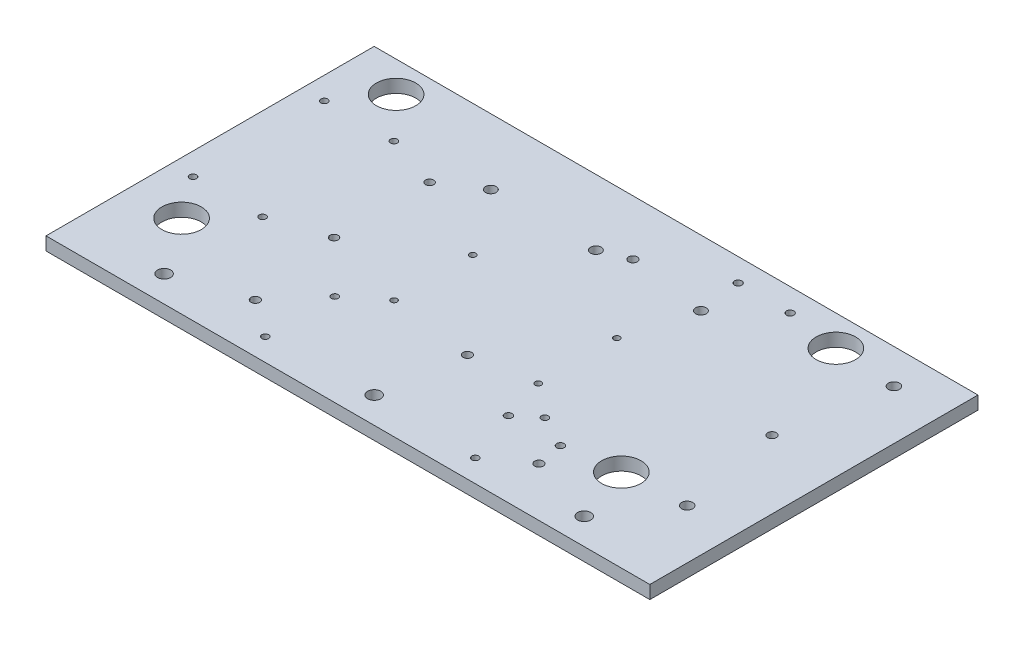
SolidWorks part; units mm, degrees
ref_plane "Front Plane" through (0, 0, 0) normal (0, 0, 1) x (1, 0, 0)
ref_plane "Top Plane" through (0, 0, 0) normal (0, 1, 0) x (1, 0, 0)
ref_plane "Right Plane" through (0, 0, 0) normal (1, 0, 0) x (0, 0, -1)
sketch "Sketch1" plane through (0, 0, 0) normal (0, 1, 0) x (1, 0, 0)
  line L1 (0, 0) -> (292.1, 0)
  line L2 (0, 0) -> (0, 158.75)
  line L3 (0, 158.75) -> (292.1, 158.75)
  line L4 (292.1, 0) -> (292.1, 158.75)
  dimension "D1" = 292.1
  dimension "D2" = 158.75
extrude "Boss-Extrude1" add sketch "Sketch1" along normal blind 6.35
sketch "Sketch2" plane through (0, 6.35, 0) normal (0, 1, 0) x (1, 0, 0)
  line L0 (0, 25.4) -> (292.1, 25.4) construction
  line L1 (0, 12.7) -> (292.1, 12.7) construction
  line L2 (146.05, 0) -> (146.05, 158.75) construction
  line L4 (0, 158.75) -> (0, 0)
  line L5 (0, 0) -> (292.1, 0)
  line L6 (292.1, 0) -> (292.1, 158.75)
  line L7 (292.1, 158.75) -> (0, 158.75)
  line L8 (0, 158.75) -> (0, 0) construction
  line L9 (0, 0) -> (292.1, 0) construction
  line L10 (292.1, 0) -> (292.1, 158.75) construction
  line L11 (292.1, 158.75) -> (0, 158.75) construction
  circle A0 centre (146.05, 12.7) radius 3.175
  circle A1 centre (247.65, 12.7) radius 3.175
  circle A2 centre (44.45, 12.7) radius 3.175
  dimension "D6" = 6.35
  dimension "D7" = 6.35
  dimension "D8" = 6.35
  dimension "D2" = 25.4
  dimension "D3" = 12.7
  dimension "D4" = 101.6
  dimension "D5" = 101.6
  dimension "D1" = 0
extrude "Cut-Extrude2" cut sketch "Sketch2" against normal blind 6.35
sketch "Sketch5" [suppressed] plane through (0, 6.35, 0) normal (0, 1, 0) x (1, 0, 0)
  line L0 (0, 0) -> (292.1, 0) construction
  line L1 (279.4, 31.75) -> (143.9, 31.75) construction
  line L2 (279.4, 31.75) -> (279.4, 75.25) construction
  line L3 (279.4, 75.25) -> (143.9, 75.25) construction
  line L4 (143.9, 31.75) -> (143.9, 75.25) construction
  line L5 (292.1, 0) -> (292.1, 158.75) construction
  circle A0 centre (279.4, 31.75) radius 1.525
  circle A1 centre (279.4, 75.25) radius 1.525
  circle A2 centre (143.9, 75.25) radius 1.525
  circle A3 centre (143.9, 31.75) radius 1.525
  dimension "D3" = 3.05
  dimension "D1" = 43.5
  dimension "D2" = 135.5
  dimension "D4" = 31.75
  dimension "D5" = 12.7
sketch "Sketch6" plane through (0, 6.35, 0) normal (0, 1, 0) x (1, 0, 0)
  line L0 (238.125, 158.75) -> (238.125, 0) construction
  line L1 (292.1, 158.75) -> (0, 158.75) construction
  line L2 (0, 0) -> (292.1, 0) construction
  line L4 (146.05, 158.75) -> (146.05, 0) construction
  line L5 (0, 25.4) -> (292.1, 25.4) construction
  line L6 (0, 158.75) -> (0, 0) construction
  line L7 (292.1, 0) -> (292.1, 158.75) construction
  line L8 (25.4, 40.1879) -> (238.125, 40.1879) construction
  line L9 (25.4, 143.9621) -> (238.125, 143.9621) construction
  line L10 (0, 92.075) -> (292.1, 92.075) construction
  line L11 (0, 158.75) -> (0, 25.4) construction
  line L12 (25.4, 143.9621) -> (25.4, 92.075) construction
  line L13 (25.4, 92.075) -> (25.4, 40.1879) construction
  circle A0 centre (25.4, 40.1879) radius 9.525
  circle A1 centre (238.125, 40.1879) radius 9.525
  circle A2 centre (25.4, 143.9621) radius 9.525
  circle A3 centre (238.125, 143.9621) radius 9.525
  point P6 (0, 0)
  dimension "D2" = 19.05
  dimension "D3" = 19.05
  dimension "D1" = 25.4
  dimension "D4" = 25.4
  dimension "D5" = 53.975
extrude "Cut-Extrude3" cut sketch "Sketch6" against normal through all
sketch "Sketch8" plane through (0, 6.35, 0) normal (0, 1, 0) x (1, 0, 0)
  line L0 (265.43, 121.908) -> (265.43, 112.242) construction
  line L1 (270.764, 112.242) -> (270.764, 121.908) construction
  line L2 (265.43, 96.908) -> (265.43, 87.242)
  line L3 (270.764, 87.242) -> (270.764, 96.908)
  line L4 (265.43, 96.908) -> (265.43, 87.242) construction
  line L5 (270.764, 87.242) -> (270.764, 96.908) construction
  line L6 (265.43, 146.908) -> (265.43, 137.242) construction
  line L7 (270.764, 137.242) -> (270.764, 146.908) construction
  line L8 (265.43, 96.908) -> (265.43, 87.242) construction
  line L9 (270.764, 87.242) -> (270.764, 96.908) construction
  line L10 (265.43, 121.908) -> (265.43, 112.242) construction
  line L11 (270.764, 112.242) -> (270.764, 121.908) construction
  line L12 (265.43, 71.908) -> (265.43, 62.242) construction
  line L13 (270.764, 62.242) -> (270.764, 71.908) construction
  line L14 (265.43, 96.908) -> (265.43, 87.242) construction
  line L15 (270.764, 87.242) -> (270.764, 96.908) construction
  line L16 (265.43, 71.908) -> (265.43, 62.242) construction
  line L17 (270.764, 62.242) -> (270.764, 71.908) construction
  line L18 (265.43, 46.908) -> (265.43, 37.242) construction
  line L19 (270.764, 37.242) -> (270.764, 46.908) construction
  line L20 (265.43, 96.908) -> (265.43, 121.908) construction
  line L21 (268.097, 137.242) -> (268.097, 146.908) construction
  line L22 (268.097, 37.242) -> (268.097, 46.908) construction
  line L23 (143.764, 129.54) -> (134.239, 129.54) construction
  line L24 (134.239, 124.46) -> (143.764, 124.46) construction
  line L25 (213.1283, 38.3159) -> (211.5027, 38.3159)
  line L26 (211.5027, 34.7345) -> (213.1283, 34.7345)
  line L27 (222.285, 31.6611) -> (222.285, 152.4889)
  line L28 (222.285, 152.4889) -> (177.2, 152.4889)
  line L29 (177.2, 152.4889) -> (177.2, 31.6611)
  line L30 (177.2, 31.6611) -> (222.285, 31.6611)
  line L31 (222.285, 31.6611) -> (222.285, 152.4889) construction
  line L32 (222.285, 152.4889) -> (177.2, 152.4889) construction
  line L33 (177.2, 152.4889) -> (177.2, 31.6611) construction
  line L34 (177.2, 31.6611) -> (222.285, 31.6611) construction
  line L35 (213.1283, 38.3159) -> (211.5027, 38.3159) construction
  line L36 (211.5027, 34.7345) -> (213.1283, 34.7345) construction
  line L37 (187.9823, 38.3159) -> (186.3567, 38.3159)
  line L38 (186.3567, 34.7345) -> (187.9823, 34.7345)
  line L39 (187.9823, 38.3159) -> (186.3567, 38.3159) construction
  line L40 (186.3567, 34.7345) -> (187.9823, 34.7345) construction
  line L41 (211.5027, 145.8341) -> (213.1283, 145.8341)
  line L42 (213.1283, 149.4155) -> (211.5027, 149.4155)
  line L43 (211.5027, 145.8341) -> (213.1283, 145.8341) construction
  line L44 (213.1283, 149.4155) -> (211.5027, 149.4155) construction
  line L45 (186.3567, 145.8341) -> (187.9823, 145.8341)
  line L46 (187.9823, 149.4155) -> (186.3567, 149.4155)
  line L47 (186.3567, 145.8341) -> (187.9823, 145.8341) construction
  line L48 (187.9823, 149.4155) -> (186.3567, 149.4155) construction
  line L49 (194.564, 129.54) -> (185.039, 129.54)
  line L50 (185.039, 124.46) -> (194.564, 124.46)
  line L51 (194.564, 129.54) -> (185.039, 129.54) construction
  line L52 (185.039, 124.46) -> (194.564, 124.46) construction
  line L53 (92.964, 129.54) -> (83.439, 129.54) construction
  line L54 (83.439, 124.46) -> (92.964, 124.46) construction
  line L55 (194.564, 129.54) -> (143.764, 129.54) construction
  line L56 (83.439, 127) -> (194.564, 127) construction
  line L57 (189.8015, 124.46) -> (189.8015, 129.54) construction
  line L58 (88.2015, 124.46) -> (88.2015, 129.54) construction
  line L63 (109.05, 54.7) -> (183.05, 54.7)
  line L64 (183.05, 54.7) -> (183.05, 97.7)
  line L65 (183.05, 97.7) -> (109.05, 97.7)
  line L66 (109.05, 97.7) -> (109.05, 54.7)
  line L67 (109.05, 54.7) -> (183.05, 54.7) construction
  line L68 (183.05, 54.7) -> (183.05, 97.7) construction
  line L69 (183.05, 97.7) -> (109.05, 97.7) construction
  line L70 (109.05, 97.7) -> (109.05, 54.7) construction
  line L82 (186.3567, 36.5252) -> (187.9823, 36.5252) construction
  line L83 (211.5027, 36.5252) -> (213.1283, 36.5252) construction
  line L84 (211.5027, 147.6248) -> (213.1283, 147.6248) construction
  line L85 (186.3567, 147.6248) -> (187.9823, 147.6248) construction
  line L88 (70.3882, 66.9707) -> (81.4118, 66.9707)
  line L89 (81.4118, 70.9077) -> (70.3882, 70.9077)
  line L90 (70.3882, 66.9707) -> (81.4118, 66.9707) construction
  line L91 (81.4118, 70.9077) -> (70.3882, 70.9077) construction
  line L92 (77.8685, 63.0845) -> (77.8685, 68.9392)
  line L93 (73.9315, 68.9392) -> (73.9315, 63.0845)
  line L94 (126.4, 44.9707) -> (126.4, 139.1793)
  line L95 (25.4, 44.9707) -> (126.4, 44.9707)
  line L96 (25.4, 139.1793) -> (25.4, 44.9707)
  line L97 (126.4, 139.1793) -> (25.4, 139.1793)
  line L98 (126.4, 44.9707) -> (126.4, 139.1793) construction
  line L99 (25.4, 44.9707) -> (126.4, 44.9707) construction
  line L100 (25.4, 139.1793) -> (25.4, 44.9707) construction
  line L101 (126.4, 139.1793) -> (25.4, 139.1793) construction
  line L102 (77.8685, 63.0845) -> (77.8685, 68.9392) construction
  line L103 (73.9315, 68.9392) -> (73.9315, 63.0845) construction
  line L104 (73.9315, 115.2108) -> (73.9315, 109.3561)
  line L105 (77.8685, 109.3561) -> (77.8685, 115.2108)
  line L106 (73.9315, 115.2108) -> (73.9315, 109.3561) construction
  line L107 (77.8685, 109.3561) -> (77.8685, 115.2108) construction
  line L108 (70.3882, 113.2423) -> (81.4118, 113.2423)
  line L109 (81.4118, 117.1793) -> (70.3882, 117.1793)
  line L110 (70.3882, 113.2423) -> (81.4118, 113.2423) construction
  line L111 (81.4118, 117.1793) -> (70.3882, 117.1793) construction
  arc A0 (265.43, 112.242) -> (270.764, 112.242) centre (268.097, 112.242) ccw construction
  arc A1 (270.764, 121.908) -> (265.43, 121.908) centre (268.097, 121.908) ccw construction
  arc A2 (265.43, 87.242) -> (270.764, 87.242) centre (268.097, 87.242) ccw
  arc A3 (270.764, 96.908) -> (265.43, 96.908) centre (268.097, 96.908) ccw
  arc A4 (265.43, 87.242) -> (270.764, 87.242) centre (268.097, 87.242) ccw construction
  arc A5 (270.764, 96.908) -> (265.43, 96.908) centre (268.097, 96.908) ccw construction
  arc A6 (265.43, 137.242) -> (270.764, 137.242) centre (268.097, 137.242) ccw construction
  arc A7 (270.764, 146.908) -> (265.43, 146.908) centre (268.097, 146.908) ccw construction
  arc A8 (265.43, 87.242) -> (270.764, 87.242) centre (268.097, 87.242) ccw construction
  arc A9 (270.764, 96.908) -> (265.43, 96.908) centre (268.097, 96.908) ccw construction
  arc A10 (265.43, 112.242) -> (270.764, 112.242) centre (268.097, 112.242) ccw construction
  arc A11 (270.764, 121.908) -> (265.43, 121.908) centre (268.097, 121.908) ccw construction
  arc A12 (265.43, 62.242) -> (270.764, 62.242) centre (268.097, 62.242) ccw construction
  arc A13 (270.764, 71.908) -> (265.43, 71.908) centre (268.097, 71.908) ccw construction
  arc A14 (265.43, 87.242) -> (270.764, 87.242) centre (268.097, 87.242) ccw construction
  arc A15 (270.764, 96.908) -> (265.43, 96.908) centre (268.097, 96.908) ccw construction
  arc A16 (265.43, 62.242) -> (270.764, 62.242) centre (268.097, 62.242) ccw construction
  arc A17 (270.764, 71.908) -> (265.43, 71.908) centre (268.097, 71.908) ccw construction
  arc A18 (265.43, 37.242) -> (270.764, 37.242) centre (268.097, 37.242) ccw construction
  arc A19 (270.764, 46.908) -> (265.43, 46.908) centre (268.097, 46.908) ccw construction
  circle A20 centre (268.097, 42.075) radius 2.667
  circle A21 centre (268.097, 142.075) radius 2.667
  arc A22 (134.239, 129.54) -> (134.239, 124.46) centre (134.239, 127) ccw construction
  arc A23 (143.764, 124.46) -> (143.764, 129.54) centre (143.764, 127) ccw construction
  arc A24 (211.5027, 38.3159) -> (211.5027, 34.7345) centre (211.5027, 36.5252) ccw
  arc A25 (213.1283, 34.7345) -> (213.1283, 38.3159) centre (213.1283, 36.5252) ccw
  arc A26 (211.5027, 38.3159) -> (211.5027, 34.7345) centre (211.5027, 36.5252) ccw construction
  arc A27 (213.1283, 34.7345) -> (213.1283, 38.3159) centre (213.1283, 36.5252) ccw construction
  arc A28 (187.9823, 34.7345) -> (187.9823, 38.3159) centre (187.9823, 36.5252) ccw
  arc A29 (186.3567, 38.3159) -> (186.3567, 34.7345) centre (186.3567, 36.5252) ccw
  arc A30 (187.9823, 34.7345) -> (187.9823, 38.3159) centre (187.9823, 36.5252) ccw construction
  arc A31 (186.3567, 38.3159) -> (186.3567, 34.7345) centre (186.3567, 36.5252) ccw construction
  arc A32 (211.5027, 149.4155) -> (211.5027, 145.8341) centre (211.5027, 147.6248) ccw
  arc A33 (213.1283, 145.8341) -> (213.1283, 149.4155) centre (213.1283, 147.6248) ccw
  arc A34 (211.5027, 149.4155) -> (211.5027, 145.8341) centre (211.5027, 147.6248) ccw construction
  arc A35 (213.1283, 145.8341) -> (213.1283, 149.4155) centre (213.1283, 147.6248) ccw construction
  arc A36 (187.9823, 145.8341) -> (187.9823, 149.4155) centre (187.9823, 147.6248) ccw
  arc A37 (186.3567, 149.4155) -> (186.3567, 145.8341) centre (186.3567, 147.6248) ccw
  arc A38 (187.9823, 145.8341) -> (187.9823, 149.4155) centre (187.9823, 147.6248) ccw construction
  arc A39 (186.3567, 149.4155) -> (186.3567, 145.8341) centre (186.3567, 147.6248) ccw construction
  arc A40 (185.039, 129.54) -> (185.039, 124.46) centre (185.039, 127) ccw
  arc A41 (194.564, 124.46) -> (194.564, 129.54) centre (194.564, 127) ccw
  arc A42 (185.039, 129.54) -> (185.039, 124.46) centre (185.039, 127) ccw construction
  arc A43 (194.564, 124.46) -> (194.564, 129.54) centre (194.564, 127) ccw construction
  arc A44 (83.439, 129.54) -> (83.439, 124.46) centre (83.439, 127) ccw construction
  arc A45 (92.964, 124.46) -> (92.964, 129.54) centre (92.964, 127) ccw construction
  circle A46 centre (189.8015, 127) radius 2.54
  circle A47 centre (139.0015, 127) radius 2.54
  circle A48 centre (88.2015, 127) radius 2.54
  circle A50 centre (111.2, 57.2) radius 1.5
  circle A51 centre (111.2, 57.2) radius 1.5
  circle A52 centre (180.9, 57.2) radius 1.5
  circle A53 centre (180.9, 57.2) radius 1.5
  circle A54 centre (180.9, 95.2) radius 1.5
  circle A55 centre (180.9, 95.2) radius 1.5
  circle A56 centre (111.2, 95.2) radius 1.5
  circle A57 centre (111.2, 95.2) radius 1.5
  circle A58 centre (95.25, 10.795) radius 1.651
  circle A59 centre (95.25, 10.795) radius 1.651
  circle A60 centre (196.85, 10.795) radius 1.651
  circle A61 centre (196.85, 10.795) radius 1.651
  circle A62 centre (196.85, 44.45) radius 1.651
  circle A63 centre (196.85, 44.45) radius 1.651
  circle A64 centre (95.25, 44.45) radius 1.651
  circle A65 centre (95.25, 44.45) radius 1.651
  circle A66 centre (10.795, 123.825) radius 1.651
  circle A67 centre (10.795, 123.825) radius 1.651
  circle A68 centre (10.795, 60.325) radius 1.651
  circle A69 centre (10.795, 60.325) radius 1.651
  circle A70 centre (44.45, 60.325) radius 1.651
  circle A71 centre (44.45, 60.325) radius 1.651
  circle A72 centre (44.45, 123.825) radius 1.651
  circle A73 centre (44.45, 123.825) radius 1.651
  circle A74 centre (77.451, 23.8125) radius 2.0955
  circle A75 centre (77.451, 23.8125) radius 2.0955
  circle A77 centre (151.8, 132.099) radius 2.0955
  circle A78 centre (151.8, 132.099) radius 2.0955
  circle A80 centre (214.649, 23.8125) radius 2.0955
  circle A81 centre (214.649, 23.8125) radius 2.0955
  circle A83 centre (151.8, 52.051) radius 2.0955
  circle A84 centre (151.8, 52.051) radius 2.0955
  circle A86 centre (259.099, 92.075) radius 2.0955
  circle A87 centre (259.099, 92.075) radius 2.0955
  circle A88 centre (187.1695, 36.5252) radius 1.7907
  circle A89 centre (212.3155, 36.5252) radius 1.7907
  circle A90 centre (212.3155, 147.6248) radius 1.7907
  circle A91 centre (187.1695, 147.6248) radius 1.7907
  circle A92 centre (70.3882, 115.2108) radius 1.9685
  circle A93 centre (75.9, 68.9392) radius 3.3274
  circle A94 centre (75.9, 68.9392) radius 3.3274 construction
  circle A95 centre (75.9, 115.2108) radius 3.3274
  arc A96 (81.4118, 66.9707) -> (81.4118, 70.9077) centre (81.4118, 68.9392) ccw
  arc A97 (70.3882, 70.9077) -> (70.3882, 66.9707) centre (70.3882, 68.9392) ccw
  arc A98 (81.4118, 66.9707) -> (81.4118, 70.9077) centre (81.4118, 68.9392) ccw construction
  arc A99 (70.3882, 70.9077) -> (70.3882, 66.9707) centre (70.3882, 68.9392) ccw construction
  arc A100 (73.9315, 63.0845) -> (77.8685, 63.0845) centre (75.9, 63.0845) ccw
  arc A101 (77.8685, 68.9392) -> (73.9315, 68.9392) centre (75.9, 68.9392) ccw
  arc A102 (73.9315, 63.0845) -> (77.8685, 63.0845) centre (75.9, 63.0845) ccw construction
  arc A103 (77.8685, 68.9392) -> (73.9315, 68.9392) centre (75.9, 68.9392) ccw construction
  circle A104 centre (75.9, 115.2108) radius 3.3274 construction
  circle A105 centre (70.3882, 68.9392) radius 1.9685
  arc A106 (73.9315, 109.3561) -> (77.8685, 109.3561) centre (75.9, 109.3561) ccw
  arc A107 (77.8685, 115.2108) -> (73.9315, 115.2108) centre (75.9, 115.2108) ccw
  arc A108 (73.9315, 109.3561) -> (77.8685, 109.3561) centre (75.9, 109.3561) ccw construction
  arc A109 (77.8685, 115.2108) -> (73.9315, 115.2108) centre (75.9, 115.2108) ccw construction
  arc A110 (81.4118, 113.2423) -> (81.4118, 117.1793) centre (81.4118, 115.2108) ccw
  arc A111 (70.3882, 117.1793) -> (70.3882, 113.2423) centre (70.3882, 115.2108) ccw
  arc A112 (81.4118, 113.2423) -> (81.4118, 117.1793) centre (81.4118, 115.2108) ccw construction
  arc A113 (70.3882, 117.1793) -> (70.3882, 113.2423) centre (70.3882, 115.2108) ccw construction
  dimension "D4" = 25
  dimension "D12" = 50.8
  dimension "D1" = 0
  dimension "D5" = 0
  dimension "D6" = 0
  dimension "D7" = 0
  dimension "D8" = 0
  dimension "D9" = 0
  dimension "D10" = 0
  dimension "D13" = 0
  dimension "D14" = 0
  dimension "D15" = 0
  dimension "D16" = 0
  dimension "D17" = 0
  dimension "D18" = 0
  dimension "D19" = 0
  dimension "D20" = 0
  dimension "D21" = 0
  dimension "D22" = 0
  dimension "D23" = 0
  dimension "D24" = 0
  dimension "D25" = 0
  dimension "D26" = 0
  dimension "D27" = 0
  dimension "D28" = 0
  dimension "D29" = 0
  dimension "D30" = 0
  dimension "D31" = 0
  dimension "D32" = 0
  dimension "D33" = 0
  dimension "D34" = 0
  dimension "D35" = 0
  dimension "D36" = 0
  dimension "D37" = 0
  dimension "D2" = 3
  dimension "D3" = 3
  dimension "D11" = 3
extrude "Cut-Extrude4" cut sketch "Sketch8" against normal through all
equation "\"D5@Sketch2\"=\"D4@Sketch2\""
equation "\"D7@Sketch2\"=\"D6@Sketch2\""
equation "\"D8@Sketch2\"=\"D7@Sketch2\""
equation "\"D4@Sketch5\"=1.25*25.4"
